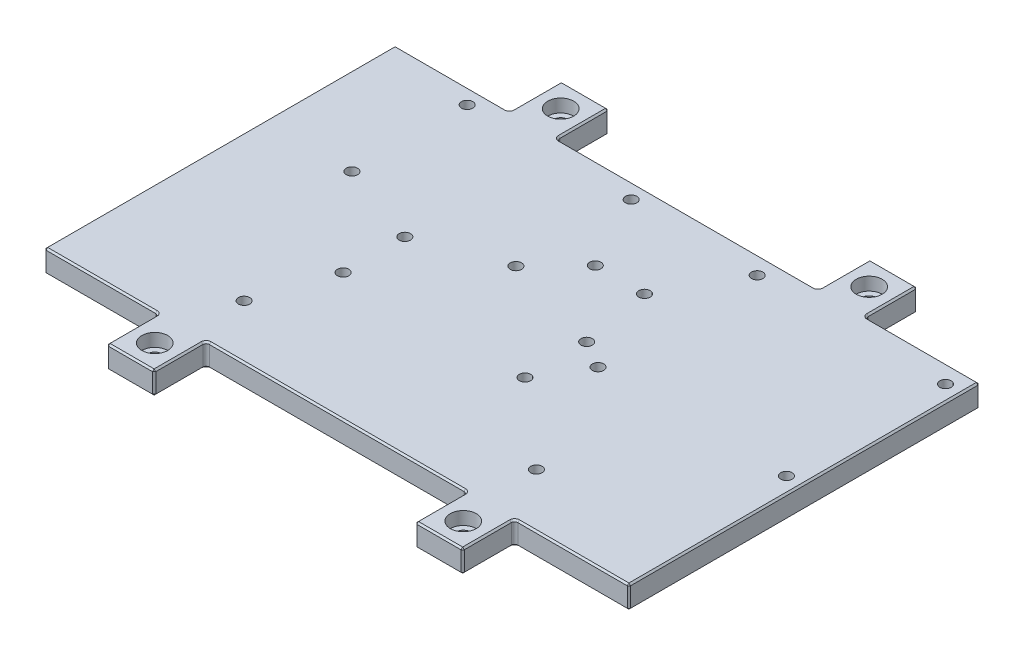
SolidWorks part; units mm, degrees
ref_plane "Front Plane" through (0, 0, 0) normal (0, 0, 1) x (1, 0, 0)
ref_plane "Top Plane" through (0, 0, 0) normal (0, 1, 0) x (1, 0, 0)
ref_plane "Right Plane" through (0, 0, 0) normal (1, 0, 0) x (0, 0, -1)
sketch "Sketch1" plane through (0, 0, 0) normal (0, 1, 0) x (1, 0, 0)
  line L0 (43.5755, 54) -> (43.5755, 70)
  line L1 (-101.2245, 54) -> (-66.0245, 54)
  line L2 (-101.2245, 54) -> (-101.2245, -54)
  line L3 (-101.2245, -54) -> (-66.0245, -54)
  line L4 (78.7755, 54) -> (78.7755, -54)
  line L5 (44.2755, 70) -> (28.2755, 70) construction
  line L6 (43.5755, 70) -> (28.9755, 70)
  line L7 (28.9755, 70) -> (28.9755, 54)
  line L9 (-51.2245, 69.5) -> (-51.2245, 55.5) construction
  line L11 (43.5755, -54) -> (43.5755, -70)
  line L12 (28.2755, -70) -> (44.2755, -70) construction
  line L13 (43.5755, -70) -> (28.9755, -70)
  line L14 (28.9755, -70) -> (28.9755, -54)
  line L16 (-51.4245, -54) -> (-51.4245, -70)
  line L18 (-65.5245, -70) -> (-51.9245, -70) construction
  line L19 (-51.4245, -70) -> (-66.0245, -70)
  line L20 (-66.0245, -70) -> (-66.0245, -54)
  line L21 (-51.2245, -55.5) -> (-51.2245, -69.5) construction
  line L22 (-66.2245, -69.5) -> (-66.2245, -55.5) construction
  line L23 (-51.4245, 54) -> (-51.4245, 70)
  line L24 (-51.9245, 70) -> (-65.5245, 70) construction
  line L25 (-51.4245, 70) -> (-66.0245, 70)
  line L26 (-66.0245, 70) -> (-66.0245, 54)
  line L27 (28.2755, 55) -> (-50.7245, 55) construction
  line L28 (-66.2245, 55.5) -> (-66.2245, 69.5) construction
  line L29 (-51.4245, -54) -> (28.9755, -54)
  line L30 (43.5755, -54) -> (78.7755, -54)
  line L31 (43.5755, 54) -> (78.7755, 54)
  line L32 (-51.4245, 54) -> (28.9755, 54)
  line L34 (43.7755, -69.5) -> (43.7755, -55.5) construction
  line L36 (43.7755, 55.5) -> (43.7755, 69.5) construction
  line L37 (28.7755, 69.5) -> (28.7755, 55.5) construction
  line L38 (28.7755, -55.5) -> (28.7755, -69.5) construction
  point P6 (78.7755, 0)
  dimension "D1" = 0.2
  dimension "D2" = 0.2
  dimension "D3" = 0.2
  dimension "D4" = 0.2
  dimension "D5" = 0.2
  dimension "D6" = 0.2
  dimension "D7" = 0.2
  dimension "D8" = 0.2
  dimension "D9" = 1
  dimension "D10" = 180
extrude "Boss-Extrude1" add sketch "Sketch1" along normal up to surface (7 mm away) contours L13 L14 L3 L11 | L19 L20 L3 L16 | L26 L25 L23 L1 | L7 L6 L0 L1
sketch "Sketch3" plane through (0, 0, 0) normal (0, -1, 0) x (1, 0, 0)
  line L0 (78.7755, -54) -> (78.7755, 54) construction
  line L1 (43.5755, 54) -> (78.7755, 54) construction
  line L2 (-56.2245, 37.5) -> (33.7755, 37.5) construction
  line L3 (15.9755, 0.7) -> (15.9755, -48.3) construction
  line L4 (15.9755, -48.3) -> (73.9755, -48.3) construction
  line L5 (73.9755, -48.3) -> (73.9755, 0.7) construction
  line L6 (73.9755, 0.7) -> (15.9755, 0.7) construction
  line L7 (15.9755, 0.7) -> (73.9755, -48.3) construction
  line L8 (73.9755, 0.7) -> (15.9755, -48.3) construction
  line L9 (-11.5745, -26) -> (3.5755, -26) construction
  line L10 (7.4755, 14.7) -> (-48.5245, 14.7) construction
  line L11 (-48.5245, 14.7) -> (-48.5245, -4.3) construction
  line L12 (-48.5245, -4.3) -> (7.4755, -4.3) construction
  line L13 (7.4755, -4.3) -> (7.4755, 14.7) construction
  line L14 (7.4755, 14.7) -> (-48.5245, -4.3) construction
  line L15 (7.4755, -4.3) -> (-48.5245, 14.7) construction
  line L16 (-74.1245, -49.1) -> (-23.6245, -49.1) construction
  line L17 (-23.6245, -49.1) -> (-23.6245, -13.6) construction
  line L18 (-23.6245, -13.6) -> (-74.1245, -13.6) construction
  line L19 (-74.1245, -13.6) -> (-74.1245, -49.1) construction
  line L20 (-74.1245, -49.1) -> (-23.6245, -13.6) construction
  line L21 (-74.1245, -13.6) -> (-23.6245, -49.1) construction
  line L22 (-51.4245, 54) -> (28.9755, 54) construction
  circle A0 centre (33.7755, 37.5) radius 1.75
  circle A1 centre (-56.2245, 37.5) radius 1.75
  circle A2 centre (73.9755, 0.7) radius 1.75
  circle A3 centre (73.9755, -48.3) radius 1.75
  circle A4 centre (15.9755, -48.3) radius 1.75
  circle A5 centre (15.9755, 0.7) radius 1.75
  circle A6 centre (-48.5245, -4.3) radius 1.75
  circle A7 centre (-48.5245, 14.7) radius 1.75
  circle A8 centre (7.4755, 14.7) radius 1.75
  circle A9 centre (7.4755, -4.3) radius 1.75
  circle A10 centre (-23.6245, -13.6) radius 1.75
  circle A11 centre (-23.6245, -49.1) radius 1.75
  circle A12 centre (-74.1245, -49.1) radius 1.75
  circle A13 centre (-74.1245, -13.6) radius 1.75
  circle A14 centre (-11.5745, -26) radius 1.75
  circle A15 centre (3.5755, -26) radius 1.75
  point P28 (-11.2245, 54)
  point P31 (-11.2245, 37.5)
  dimension "D1" = 3.5
  dimension "D2" = 90
  dimension "D4" = 16.5
  dimension "D5" = 35.5
  dimension "D6" = 50.5
  dimension "D9" = 56
  dimension "D10" = 19
  dimension "D13" = 15.15
  dimension "D3" = 49
  dimension "D16" = 58
  dimension "D7" = 4.8
  dimension "D8" = 53.3
  dimension "D11" = 39.3
  dimension "D12" = 71.3
  dimension "D14" = 75.2
  dimension "D15" = 80
  dimension "D17" = 67.6
  dimension "D18" = 102.4
extrude "Cut-Extrude1" cut sketch "Sketch3" against normal through all
hole_wizard "CBORE for M4 SHCS1" positions "Sketch4" profile "Sketch5" counterbore size "M4" standard "ANSI Metric" end condition through all
sketch "Sketch4" plane through (0, 7, 0) normal (0, 1, 0) x (1, 0, 0)
  line L0 (-66.0245, -70) -> (-51.4245, -70) construction
  line L1 (28.9755, -70) -> (43.5755, -70) construction
  line L2 (-66.0245, 70) -> (-51.4245, 70) construction
  line L3 (28.9755, 70) -> (43.5755, 70) construction
  point P0 (-58.7245, 62.5)
  point P2 (36.2755, 62.5)
  point P4 (36.2755, -62.5)
  point P6 (-58.7245, -62.5)
  point P13 (36.2755, -70)
  point P14 (-58.7245, -70)
  point P19 (-58.7245, 70)
  point P22 (36.2755, 70)
  dimension "D1" = 7.5
  dimension "D2" = 7.5
sketch "Sketch5" plane through (-58.7245, 7, -62.5) normal (1, 0, 0) x (0, 0, 1)
  line L0 (0, 0) -> (0, 7)
  line L1 (0, 7) -> (2.25, 7)
  line L3 (2.25, 7) -> (2.25, 4)
  line L4 (2.25, 4) -> (4, 4)
  line L5 (4, 4) -> (4, 0)
  line L7 (4, 0) -> (0, 0)
  line L11 (0, -6.35) -> (0, 107.95) construction
  dimension "Thru Hole Dia." = 4.5
  dimension "Thru Hole Depth" = 7
  dimension "C'Bore Dia." = 8
  dimension "C'Bore Depth" = 4
fillet "Fillet1" radius 1 8 edges at (-66.0245, 3.5, 54) (-51.4245, 3.5, 54) (28.9755, 3.5, 54) (43.5755, 3.5, 54) (43.5755, 3.5, -54) (28.9755, 3.5, -54) (-66.0245, 3.5, -54) (-51.4245, 3.5, -54)
chamfer "Chamfer2" distance 0.5 angle 45 68 edges at (36.2755, 0, -70) (43.5755, 3.5, -70) (36.2755, 7, -70) (28.9755, 3.5, -70) (-51.4245, 0, -62.5) (28.9755, 0, -62.5) (-51.1316, 0, -54.2929) (28.6826, 0, -54.2929) (-11.2245, 0, -54) (28.9755, 7, -62.5) (-51.4245, 7, -62.5) (28.6826, 7, -54.2929) (-51.1316, 7, -54.2929) (-11.2245, 7, -54) (-58.7245, 0, -70) (-51.4245, 3.5, -70) (-58.7245, 7, -70) (-66.0245, 3.5, -70) (43.5755, 3.5, 70) (36.2755, 0, 70) (28.9755, 3.5, 70) (36.2755, 7, 70) (-66.0245, 0, -62.5) (-66.0245, 7, -62.5) (-66.0245, 7, 62.5) (-66.0245, 0, 62.5) (-66.3174, 0, -54.2929) (-66.3174, 7, -54.2929) (-66.3174, 7, 54.2929) (-66.3174, 0, 54.2929) (-84.1245, 0, -54) (-84.1245, 7, -54) (-101.2245, 0, 0) (-101.2245, 3.5, -54) (-101.2245, 7, 0) (-84.1245, 7, 54) (-101.2245, 3.5, 54) (-84.1245, 0, 54) (-51.4245, 3.5, 70) (-58.7245, 0, 70) (-66.0245, 3.5, 70) (-58.7245, 7, 70) (-51.4245, 0, 62.5) (28.9755, 0, 62.5) (-51.1316, 0, 54.2929) (28.6826, 0, 54.2929) (-11.2245, 0, 54) (28.9755, 7, 62.5) (-51.4245, 7, 62.5) (28.6826, 7, 54.2929) (-51.1316, 7, 54.2929) (-11.2245, 7, 54) (43.5755, 0, -62.5) (43.5755, 7, -62.5) (43.5755, 0, 62.5) (43.5755, 7, 62.5) (43.8684, 0, -54.2929) (43.8684, 7, -54.2929) (43.8684, 0, 54.2929) (43.8684, 7, 54.2929) (78.7755, 0, 0) (61.6755, 0, -54) (78.7755, 3.5, -54) (61.6755, 7, -54) (78.7755, 7, 0) (61.6755, 0, 54) (78.7755, 3.5, 54) (61.6755, 7, 54)
equation "\"M2.5 Heatset Hole\"= \"M2.5 Heatset Hole@robot.Assembly\""
equation "\"D1@Sketch3\"=\"M2.5 Heatset Hole\""
